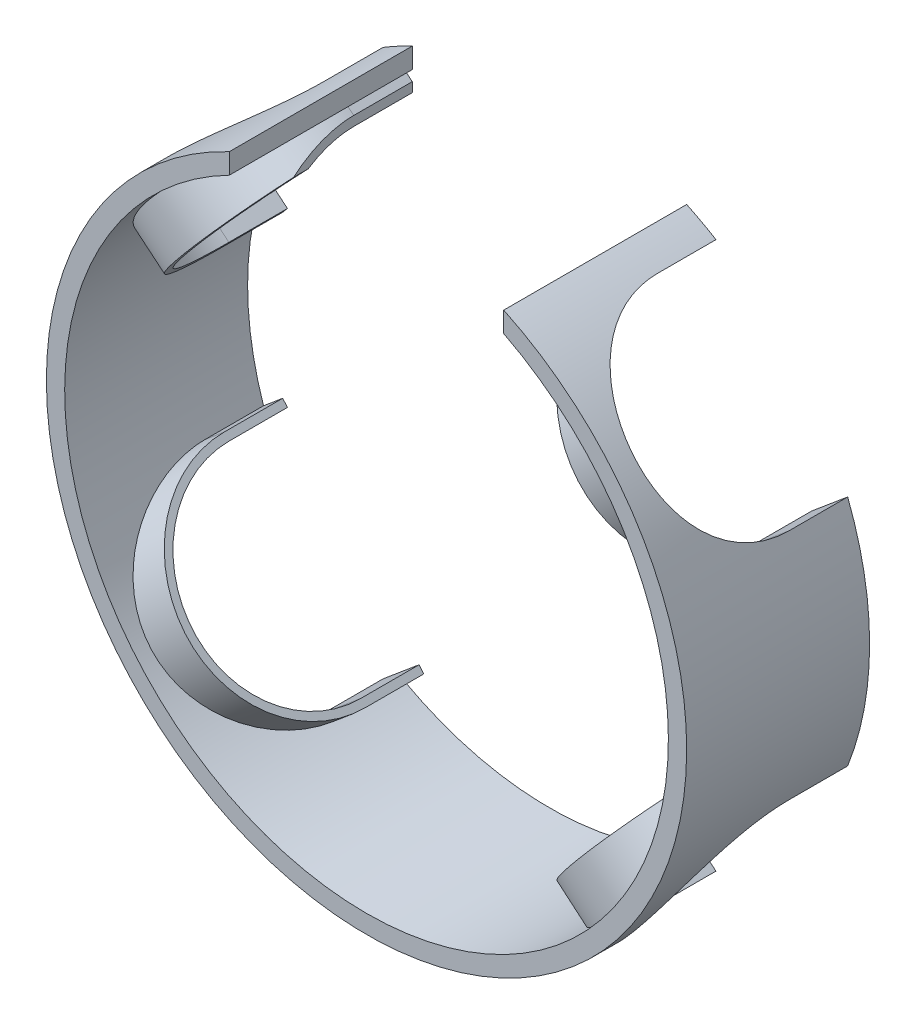
SolidWorks part; units mm, degrees
ref_plane "Front Plane" through (0, 0, 0) normal (0, 0, 1) x (1, 0, 0)
ref_plane "Top Plane" through (0, 0, 0) normal (0, 1, 0) x (1, 0, 0)
ref_plane "Right Plane" through (0, 0, 0) normal (1, 0, 0) x (0, 0, -1)
sketch "Sketch1" plane through (0, 0, 0) normal (0, 0, 1) x (1, 0, 0)
  circle A0 centre (0, 0) radius 87.5
  circle A1 centre (0, 0) radius 82.5
  dimension "D1" = 175
  dimension "D2" = 5
extrude "Boss-Extrude1" add sketch "Sketch1" along normal blind 50
sketch "Sketch2" plane through (0, 0, 0) normal (0, 1, 0) x (1, 0, 0)
  line L0 (0, 0) -> (0, -50)
  line L1 (-87.5, -50) -> (87.5, -50) construction
ref_plane "Plane1" through (0, 0, 0) normal (-0.766, 0.6428, 0) x (0, 0, 1)
sketch "Sketch3" plane through (0, 0, 0) normal (-0.766, 0.6428, 0) x (0, 0, 1)
  line L0 (0, 87.5) -> (0, -87.5) construction
  line L1 (16, 0) -> (0, 0) construction
  line L2 (16, 28) -> (-21.3159, 28)
  line L3 (-21.3159, 28) -> (-21.3159, -28)
  line L4 (-21.3159, -28) -> (16, -28)
  arc A0 (16, -28) -> (16, 28) centre (16, 0) ccw
  dimension "D2" = 56
  dimension "D1" = 16
extrude "Cut-Extrude1" cut sketch "Sketch3" along normal through all
ref_plane "Plane2" through (-53.6231, 44.9951, 0) normal (-0.766, 0.6428, 0) x (0, 0, 1)
sketch "Sketch5" plane through (-53.6231, 44.9951, 0) normal (-0.766, 0.6428, 0) x (0, 0, 1)
  line L0 (0, -28) -> (16, -28) construction
  line L1 (16, 28) -> (0, 28) construction
  line L2 (0, -28) -> (16, -28)
  line L3 (16, 28) -> (0, 28)
  line L4 (0, -30) -> (16, -30)
  line L5 (16, 30) -> (0, 30)
  line L6 (0, 28) -> (0, 30)
  line L7 (0, -28) -> (0, -30)
  arc A0 (16, -28) -> (16, 28) centre (16, 0) ccw construction
  arc A1 (16, -28) -> (16, 28) centre (16, 0) ccw
  arc A2 (16, -30) -> (16, 30) centre (16, 0) ccw
  dimension "D1" = 2
extrude "Boss-Extrude2" add sketch "Sketch5" along normal up to next
mirror "Mirror1" about plane through (0, 0, 0) normal (1, 0, 0) of "Boss-Extrude2", "Cut-Extrude1" second plane through (0, 0, 0) second plane normal (0, 1, 0)
sketch "Sketch4" plane through (0, 0, 50) normal (0, 0, 1) x (1, 0, 0)
  line L1 (-37.5, 150.5063) -> (37.5, 150.5063)
  line L2 (-37.5, 150.5063) -> (-37.5, 0)
  line L3 (-37.5, 0) -> (37.5, 0)
  line L4 (37.5, 150.5063) -> (37.5, 0)
  line L5 (-37.5, 150.5063) -> (37.5, 0) construction
  line L6 (-37.5, 0) -> (37.5, 150.5063) construction
  point P0 (0, 75.2531)
  dimension "D1" = 75
extrude "Cut-Extrude2" cut sketch "Sketch4" against normal through all
